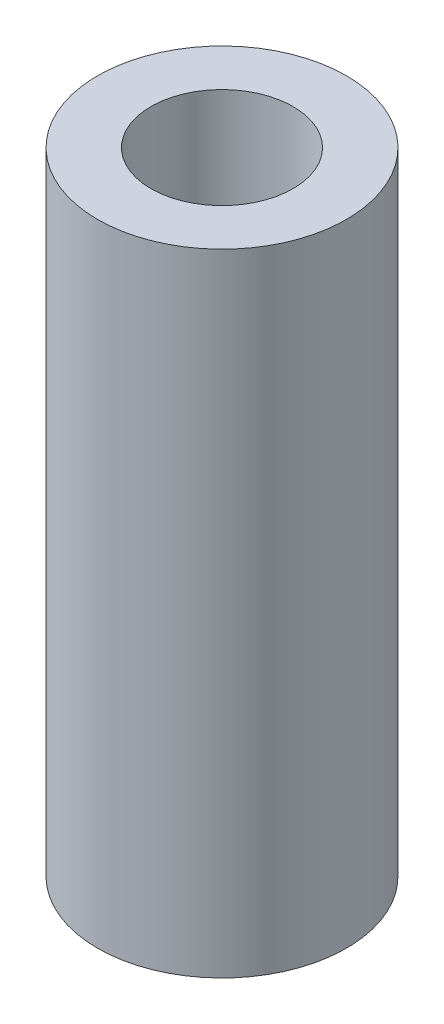
SolidWorks part; units mm, degrees
material "45"
ref_plane "前视基准面" through (0, 0, 0) normal (0, 0, 1) x (1, 0, 0)
ref_plane "上视基准面" through (0, 0, 0) normal (0, 1, 0) x (1, 0, 0)
ref_plane "右视基准面" through (0, 0, 0) normal (1, 0, 0) x (0, 0, -1)
sketch "草图1" plane through (0, 0, 0) normal (0, 0, 1) x (1, 0, 0)
  line L0 (0, 0) -> (0, 370.1352) construction
  line L2 (0, 71) -> (14, 71)
  line L3 (0, 71) -> (0, 0)
  line L4 (0, 0) -> (14, 0)
  line L5 (14, 71) -> (14, 0)
  dimension "D1" = 14
  dimension "D2" = 71
revolve "旋转1" add sketch "草图1" angle 360 about L0
sketch "草图2" plane through (0, 71, 0) normal (0, 1, 0) x (1, 0, 0)
  circle A0 centre (0, 0) radius 8
  dimension "D1" = 16
extrude "切除-拉伸1" cut sketch "草图2" against normal through all
